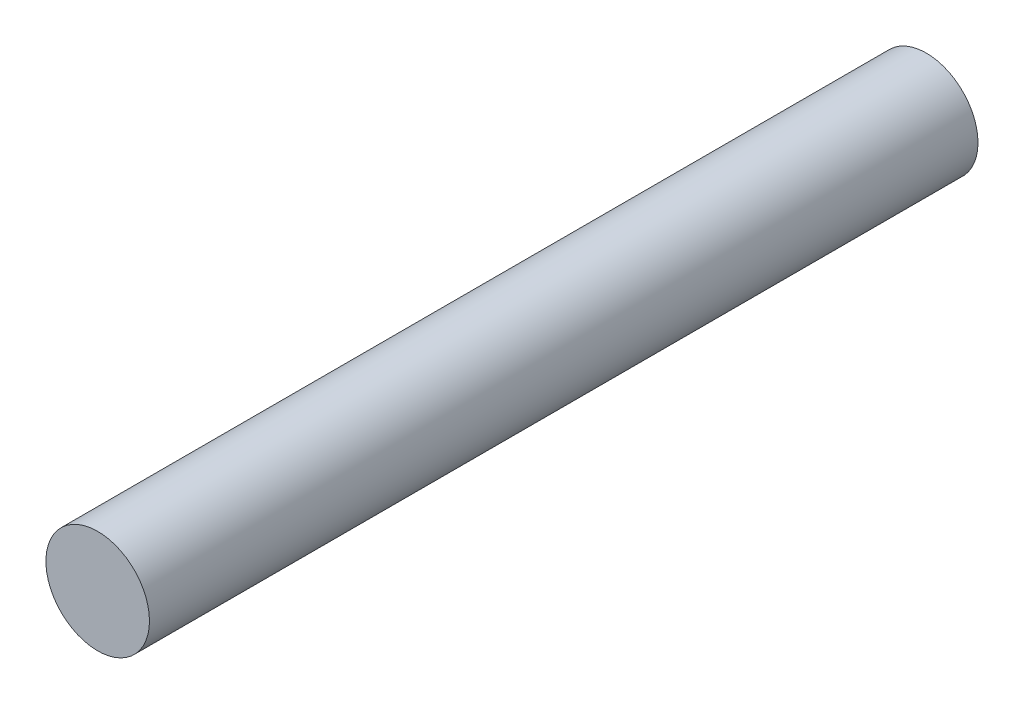
SolidWorks part; units mm, degrees
ref_plane "Front Plane" through (0, 0, 0) normal (0, 0, 1) x (1, 0, 0)
ref_plane "Top Plane" through (0, 0, 0) normal (0, 1, 0) x (1, 0, 0)
ref_plane "Right Plane" through (0, 0, 0) normal (1, 0, 0) x (0, 0, -1)
sketch "Sketch1" plane through (0, 0, 0) normal (0, 0, 1) x (1, 0, 0)
  circle A0 centre (0, 0) radius 7.5
  dimension "D1" = 7.5
extrude "Boss-Extrude1" add sketch "Sketch1" along normal blind 120
